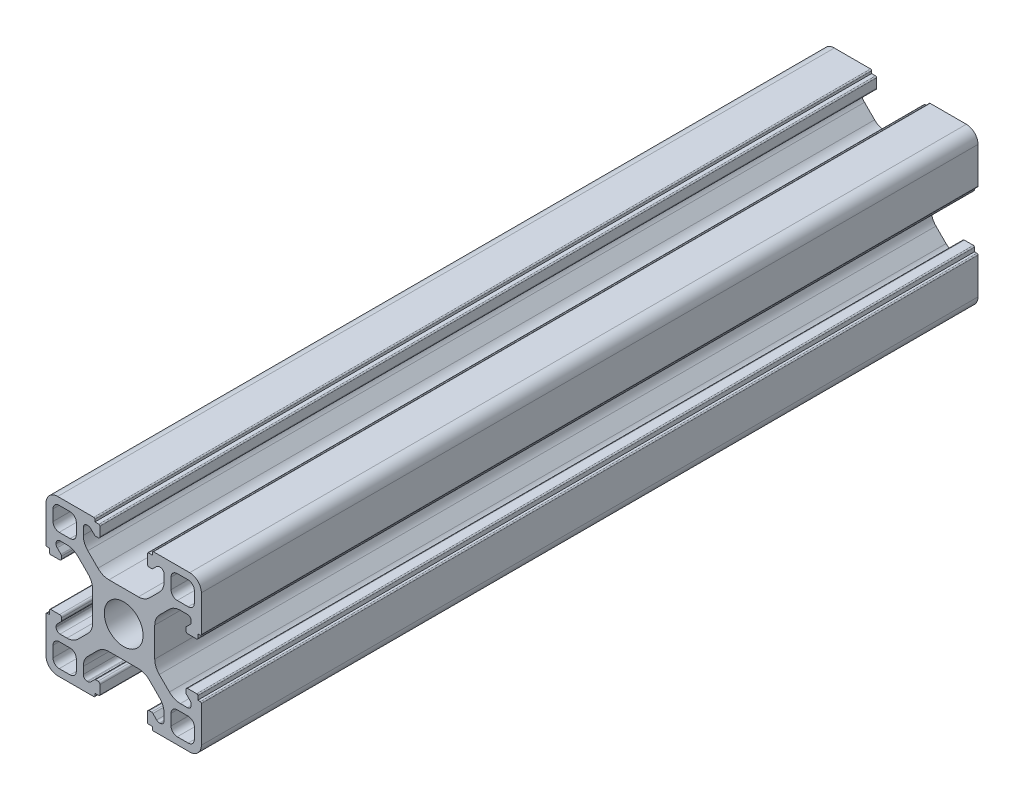
SolidWorks part; units mm, degrees
material "1060 Сплав"
ref_plane "Спереди" through (0, 0, 0) normal (0, 0, 1) x (1, 0, 0)
ref_plane "Сверху" through (0, 0, 0) normal (0, 1, 0) x (1, 0, 0)
ref_plane "Справа" through (0, 0, 0) normal (1, 0, 0) x (0, 0, -1)
sketch "Эскиз1" plane through (0, 0, 0) normal (0, 0, 1) x (1, 0, 0)
  line L0 (9.0997, 9.6536) -> (6.0997, 6.6536) construction
  line L1 (-0.0003, 4.5536) -> (1.8985, 4.5536)
  line L2 (-0.0003, 0.5536) -> (9.9997, 10.5536) construction
  line L3 (7.5997, 8.1536) -> (6.0997, 9.6536) construction
  line L4 (3.3127, 5.1394) -> (4.6139, 6.4406)
  line L5 (6.8997, 6.6536) -> (8.2997, 6.6536)
  line L6 (6.0997, 7.4536) -> (6.0997, 8.8536)
  line L7 (8.2997, 9.6536) -> (6.8997, 9.6536)
  line L8 (5.1997, 8.7536) -> (5.1997, 7.8548)
  line L9 (3.7629, 8.6268) -> (4.2433, 9.1071)
  line L10 (3.1997, 10.1027) -> (3.6997, 10.1027)
  line L11 (3.5862, 8.5536) -> (3.2997, 8.5536)
  line L12 (4.5968, 9.2536) -> (4.6997, 9.2536)
  line L13 (3.6997, 10.4036) -> (3.6997, 10.1027)
  line L14 (3.0497, 9.9527) -> (3.0497, 8.8036)
  line L15 (8.4997, 10.5536) -> (3.8497, 10.5536)
  line L16 (9.0997, 8.8536) -> (9.0997, 7.4536)
  line L17 (9.9997, 9.0536) -> (9.9997, 4.4036)
  line L18 (9.3988, 3.6036) -> (8.2497, 3.6036)
  line L19 (9.8497, 4.2536) -> (9.5488, 4.2536)
  line L20 (8.6997, 5.1507) -> (8.6997, 5.2536)
  line L21 (7.9997, 4.14) -> (7.9997, 3.8536)
  line L22 (9.5488, 3.7536) -> (9.5488, 4.2536)
  line L23 (8.0729, 4.3168) -> (8.5533, 4.7971)
  line L24 (8.1997, 5.7536) -> (7.3009, 5.7536)
  line L25 (4.5855, 3.8666) -> (5.8867, 5.1678)
  line L26 (3.9997, 0.5536) -> (3.9997, 2.4524)
  line L27 (3.9997, 0.5536) -> (3.9997, -1.3452)
  line L28 (4.5855, -2.7594) -> (5.8867, -4.0606)
  line L29 (6.0997, -6.3464) -> (6.0997, -7.7464)
  line L30 (6.8997, -5.5464) -> (8.2997, -5.5464)
  line L31 (9.0997, -7.7464) -> (9.0997, -6.3464)
  line L32 (8.1997, -4.6464) -> (7.3009, -4.6464)
  line L33 (8.0729, -3.2096) -> (8.5533, -3.69)
  line L34 (9.5488, -2.6464) -> (9.5488, -3.1464)
  line L35 (7.9997, -3.0329) -> (7.9997, -2.7464)
  line L36 (8.6997, -4.0435) -> (8.6997, -4.1464)
  line L37 (9.8497, -3.1464) -> (9.5488, -3.1464)
  line L38 (9.3988, -2.4964) -> (8.2497, -2.4964)
  line L39 (9.9997, -7.9464) -> (9.9997, -3.2964)
  line L40 (8.2997, -8.5464) -> (6.8997, -8.5464)
  line L41 (8.4997, -9.4464) -> (3.8497, -9.4464)
  line L42 (3.0497, -8.8455) -> (3.0497, -7.6964)
  line L43 (3.6997, -9.2964) -> (3.6997, -8.9955)
  line L44 (4.5968, -8.1464) -> (4.6997, -8.1464)
  line L45 (3.5862, -7.4464) -> (3.2997, -7.4464)
  line L46 (3.1997, -8.9955) -> (3.6997, -8.9955)
  line L47 (3.7629, -7.5196) -> (4.2433, -8)
  line L48 (5.1997, -7.6464) -> (5.1997, -6.7476)
  line L49 (3.3127, -4.0322) -> (4.6139, -5.3334)
  line L50 (-0.0003, -3.4464) -> (1.8985, -3.4464)
  line L51 (9.0997, -8.5464) -> (6.0997, -5.5464) construction
  line L52 (-0.0003, 0.5536) -> (9.9997, -9.4464) construction
  line L53 (7.5997, -7.0464) -> (9.0997, -5.5464) construction
  line L54 (-0.0003, -3.4464) -> (-1.8991, -3.4464)
  line L55 (-3.3133, -4.0322) -> (-4.6145, -5.3334)
  line L56 (-6.9003, -5.5464) -> (-8.3003, -5.5464)
  line L57 (-6.1003, -6.3464) -> (-6.1003, -7.7464)
  line L58 (-8.3003, -8.5464) -> (-6.9003, -8.5464)
  line L59 (-5.2003, -7.6464) -> (-5.2003, -6.7476)
  line L60 (-3.7635, -7.5196) -> (-4.2438, -8)
  line L61 (-3.2003, -8.9955) -> (-3.7003, -8.9955)
  line L62 (-3.5867, -7.4464) -> (-3.3003, -7.4464)
  line L63 (-4.5974, -8.1464) -> (-4.7003, -8.1464)
  line L64 (-3.7003, -9.2964) -> (-3.7003, -8.9955)
  line L65 (-3.0503, -8.8455) -> (-3.0503, -7.6964)
  line L66 (-8.5003, -9.4464) -> (-3.8503, -9.4464)
  line L67 (-9.1003, -7.7464) -> (-9.1003, -6.3464)
  line L68 (-10.0003, -7.9464) -> (-10.0003, -3.2964)
  line L69 (-9.3994, -2.4964) -> (-8.2503, -2.4964)
  line L70 (-9.8503, -3.1464) -> (-9.5494, -3.1464)
  line L71 (-8.7003, -4.0435) -> (-8.7003, -4.1464)
  line L72 (-8.0003, -3.0329) -> (-8.0003, -2.7464)
  line L73 (-9.5494, -2.6464) -> (-9.5494, -3.1464)
  line L74 (-8.0735, -3.2096) -> (-8.5538, -3.69)
  line L75 (-8.2003, -4.6464) -> (-7.3015, -4.6464)
  line L76 (-4.5861, -2.7594) -> (-5.8873, -4.0606)
  line L77 (-4.0003, 0.5536) -> (-4.0003, -1.3452)
  line L78 (-9.1003, -8.5464) -> (-6.1003, -5.5464) construction
  line L79 (-0.0003, 0.5536) -> (-10.0003, -9.4464) construction
  line L80 (-7.6003, -7.0464) -> (-6.1003, -8.5464) construction
  line L81 (-4.0003, 0.5536) -> (-4.0003, 2.4524)
  line L82 (-4.5861, 3.8666) -> (-5.8873, 5.1678)
  line L83 (-6.1003, 7.4536) -> (-6.1003, 8.8536)
  line L84 (-6.9003, 6.6536) -> (-8.3003, 6.6536)
  line L85 (-9.1003, 8.8536) -> (-9.1003, 7.4536)
  line L86 (-8.2003, 5.7536) -> (-7.3015, 5.7536)
  line L87 (-8.0735, 4.3168) -> (-8.5538, 4.7971)
  line L88 (-9.5494, 3.7536) -> (-9.5494, 4.2536)
  line L89 (-8.0003, 4.14) -> (-8.0003, 3.8536)
  line L90 (-8.7003, 5.1507) -> (-8.7003, 5.2536)
  line L91 (-9.8503, 4.2536) -> (-9.5494, 4.2536)
  line L92 (-9.3994, 3.6036) -> (-8.2503, 3.6036)
  line L93 (-10.0003, 9.0536) -> (-10.0003, 4.4036)
  line L94 (-8.3003, 9.6536) -> (-6.9003, 9.6536)
  line L95 (-8.5003, 10.5536) -> (-3.8503, 10.5536)
  line L96 (-3.0503, 9.9527) -> (-3.0503, 8.8036)
  line L97 (-3.7003, 10.4036) -> (-3.7003, 10.1027)
  line L98 (-4.5974, 9.2536) -> (-4.7003, 9.2536)
  line L99 (-3.5867, 8.5536) -> (-3.3003, 8.5536)
  line L100 (-3.2003, 10.1027) -> (-3.7003, 10.1027)
  line L101 (-3.7635, 8.6268) -> (-4.2438, 9.1071)
  line L102 (-5.2003, 8.7536) -> (-5.2003, 7.8548)
  line L103 (-3.3133, 5.1394) -> (-4.6145, 6.4406)
  line L104 (-0.0003, 4.5536) -> (-1.8991, 4.5536)
  line L105 (-11.7644, 0.5536) -> (11.5041, 0.5536) construction
  line L106 (-9.1003, 9.6536) -> (-6.1003, 6.6536) construction
  line L107 (-0.0003, -11.5328) -> (-0.0003, 11.2725) construction
  line L108 (-0.0003, 0.5536) -> (-10.0003, 10.5536) construction
  line L109 (-7.6003, 8.1536) -> (-9.1003, 6.6536) construction
  arc A0 (9.0997, 8.8536) -> (8.2997, 9.6536) centre (8.2997, 8.8536) ccw
  arc A1 (6.8997, 9.6536) -> (6.0997, 8.8536) centre (6.8997, 8.8536) ccw
  arc A2 (6.8997, 6.6536) -> (6.0997, 7.4536) centre (6.8997, 7.4536) cw
  arc A3 (8.4997, 10.5536) -> (9.9997, 9.0536) centre (8.4997, 9.0536) cw
  arc A4 (3.1997, 10.1027) -> (3.0497, 9.9527) centre (3.1997, 9.9527) ccw
  arc A5 (3.8497, 10.5536) -> (3.6997, 10.4036) centre (3.8497, 10.4036) ccw
  arc A6 (3.5862, 8.5536) -> (3.7629, 8.6268) centre (3.5862, 8.8036) ccw
  arc A7 (3.2997, 8.5536) -> (3.0497, 8.8036) centre (3.2997, 8.8036) cw
  arc A8 (4.2433, 9.1071) -> (4.5968, 9.2536) centre (4.5968, 8.7536) cw
  arc A9 (4.6997, 9.2536) -> (5.1997, 8.7536) centre (4.6997, 8.7536) cw
  arc A10 (2.4997, 0.5536) -> (-0.0003, 3.0536) centre (-0.0003, 0.5536) ccw
  arc A11 (1.8985, 4.5536) -> (3.3127, 5.1394) centre (1.8985, 6.5536) ccw
  arc A12 (5.1997, 7.8548) -> (4.6139, 6.4406) centre (3.1997, 7.8548) cw
  arc A13 (9.0997, 7.4536) -> (8.2997, 6.6536) centre (8.2997, 7.4536) cw
  arc A14 (8.6997, 5.2536) -> (8.1997, 5.7536) centre (8.1997, 5.2536) ccw
  arc A15 (8.5533, 4.7971) -> (8.6997, 5.1507) centre (8.1997, 5.1507) ccw
  arc A16 (7.9997, 3.8536) -> (8.2497, 3.6036) centre (8.2497, 3.8536) ccw
  arc A17 (7.9997, 4.14) -> (8.0729, 4.3168) centre (8.2497, 4.14) cw
  arc A18 (9.9997, 4.4036) -> (9.8497, 4.2536) centre (9.8497, 4.4036) cw
  arc A19 (9.5488, 3.7536) -> (9.3988, 3.6036) centre (9.3988, 3.7536) cw
  arc A20 (7.3009, 5.7536) -> (5.8867, 5.1678) centre (7.3009, 3.7536) ccw
  arc A21 (3.9997, 2.4524) -> (4.5855, 3.8666) centre (5.9997, 2.4524) cw
  arc A22 (8.2997, -8.5464) -> (9.0997, -7.7464) centre (8.2997, -7.7464) ccw
  arc A23 (9.0997, -6.3464) -> (8.2997, -5.5464) centre (8.2997, -6.3464) ccw
  arc A24 (6.0997, -6.3464) -> (6.8997, -5.5464) centre (6.8997, -6.3464) cw
  arc A25 (9.9997, -7.9464) -> (8.4997, -9.4464) centre (8.4997, -7.9464) cw
  arc A26 (9.5488, -2.6464) -> (9.3988, -2.4964) centre (9.3988, -2.6464) ccw
  arc A27 (9.9997, -3.2964) -> (9.8497, -3.1464) centre (9.8497, -3.2964) ccw
  arc A28 (7.9997, -3.0329) -> (8.0729, -3.2096) centre (8.2497, -3.0329) ccw
  arc A29 (7.9997, -2.7464) -> (8.2497, -2.4964) centre (8.2497, -2.7464) cw
  arc A30 (8.5533, -3.69) -> (8.6997, -4.0435) centre (8.1997, -4.0435) cw
  arc A31 (8.6997, -4.1464) -> (8.1997, -4.6464) centre (8.1997, -4.1464) cw
  arc A32 (-0.0003, -1.9464) -> (2.4997, 0.5536) centre (-0.0003, 0.5536) ccw
  arc A33 (3.9997, -1.3452) -> (4.5855, -2.7594) centre (5.9997, -1.3452) ccw
  arc A34 (7.3009, -4.6464) -> (5.8867, -4.0606) centre (7.3009, -2.6464) cw
  arc A35 (6.8997, -8.5464) -> (6.0997, -7.7464) centre (6.8997, -7.7464) cw
  arc A36 (4.6997, -8.1464) -> (5.1997, -7.6464) centre (4.6997, -7.6464) ccw
  arc A37 (4.2433, -8) -> (4.5968, -8.1464) centre (4.5968, -7.6464) ccw
  arc A38 (3.2997, -7.4464) -> (3.0497, -7.6964) centre (3.2997, -7.6964) ccw
  arc A39 (3.5862, -7.4464) -> (3.7629, -7.5196) centre (3.5862, -7.6964) cw
  arc A40 (3.8497, -9.4464) -> (3.6997, -9.2964) centre (3.8497, -9.2964) cw
  arc A41 (3.1997, -8.9955) -> (3.0497, -8.8455) centre (3.1997, -8.8455) cw
  arc A42 (5.1997, -6.7476) -> (4.6139, -5.3334) centre (3.1997, -6.7476) ccw
  arc A43 (1.8985, -3.4464) -> (3.3127, -4.0322) centre (1.8985, -5.4464) cw
  arc A44 (-9.1003, -7.7464) -> (-8.3003, -8.5464) centre (-8.3003, -7.7464) ccw
  arc A45 (-6.9003, -8.5464) -> (-6.1003, -7.7464) centre (-6.9003, -7.7464) ccw
  arc A46 (-6.9003, -5.5464) -> (-6.1003, -6.3464) centre (-6.9003, -6.3464) cw
  arc A47 (-8.5003, -9.4464) -> (-10.0003, -7.9464) centre (-8.5003, -7.9464) cw
  arc A48 (-3.2003, -8.9955) -> (-3.0503, -8.8455) centre (-3.2003, -8.8455) ccw
  arc A49 (-3.8503, -9.4464) -> (-3.7003, -9.2964) centre (-3.8503, -9.2964) ccw
  arc A50 (-3.5867, -7.4464) -> (-3.7635, -7.5196) centre (-3.5867, -7.6964) ccw
  arc A51 (-3.3003, -7.4464) -> (-3.0503, -7.6964) centre (-3.3003, -7.6964) cw
  arc A52 (-4.2438, -8) -> (-4.5974, -8.1464) centre (-4.5974, -7.6464) cw
  arc A53 (-4.7003, -8.1464) -> (-5.2003, -7.6464) centre (-4.7003, -7.6464) cw
  arc A54 (-2.5003, 0.5536) -> (-0.0003, -1.9464) centre (-0.0003, 0.5536) ccw
  arc A55 (-1.8991, -3.4464) -> (-3.3133, -4.0322) centre (-1.8991, -5.4464) ccw
  arc A56 (-5.2003, -6.7476) -> (-4.6145, -5.3334) centre (-3.2003, -6.7476) cw
  arc A57 (-9.1003, -6.3464) -> (-8.3003, -5.5464) centre (-8.3003, -6.3464) cw
  arc A58 (-8.7003, -4.1464) -> (-8.2003, -4.6464) centre (-8.2003, -4.1464) ccw
  arc A59 (-8.5538, -3.69) -> (-8.7003, -4.0435) centre (-8.2003, -4.0435) ccw
  arc A60 (-8.0003, -2.7464) -> (-8.2503, -2.4964) centre (-8.2503, -2.7464) ccw
  arc A61 (-8.0003, -3.0329) -> (-8.0735, -3.2096) centre (-8.2503, -3.0329) cw
  arc A62 (-10.0003, -3.2964) -> (-9.8503, -3.1464) centre (-9.8503, -3.2964) cw
  arc A63 (-9.5494, -2.6464) -> (-9.3994, -2.4964) centre (-9.3994, -2.6464) cw
  arc A64 (-7.3015, -4.6464) -> (-5.8873, -4.0606) centre (-7.3015, -2.6464) ccw
  arc A65 (-4.0003, -1.3452) -> (-4.5861, -2.7594) centre (-6.0003, -1.3452) cw
  arc A66 (-8.3003, 9.6536) -> (-9.1003, 8.8536) centre (-8.3003, 8.8536) ccw
  arc A67 (-9.1003, 7.4536) -> (-8.3003, 6.6536) centre (-8.3003, 7.4536) ccw
  arc A68 (-6.1003, 7.4536) -> (-6.9003, 6.6536) centre (-6.9003, 7.4536) cw
  arc A69 (-10.0003, 9.0536) -> (-8.5003, 10.5536) centre (-8.5003, 9.0536) cw
  arc A70 (-9.5494, 3.7536) -> (-9.3994, 3.6036) centre (-9.3994, 3.7536) ccw
  arc A71 (-10.0003, 4.4036) -> (-9.8503, 4.2536) centre (-9.8503, 4.4036) ccw
  arc A72 (-8.0003, 4.14) -> (-8.0735, 4.3168) centre (-8.2503, 4.14) ccw
  arc A73 (-8.0003, 3.8536) -> (-8.2503, 3.6036) centre (-8.2503, 3.8536) cw
  arc A74 (-8.5538, 4.7971) -> (-8.7003, 5.1507) centre (-8.2003, 5.1507) cw
  arc A75 (-8.7003, 5.2536) -> (-8.2003, 5.7536) centre (-8.2003, 5.2536) cw
  arc A76 (-0.0003, 3.0536) -> (-2.5003, 0.5536) centre (-0.0003, 0.5536) ccw
  arc A77 (-4.0003, 2.4524) -> (-4.5861, 3.8666) centre (-6.0003, 2.4524) ccw
  arc A78 (-7.3015, 5.7536) -> (-5.8873, 5.1678) centre (-7.3015, 3.7536) cw
  arc A79 (-6.9003, 9.6536) -> (-6.1003, 8.8536) centre (-6.9003, 8.8536) cw
  arc A80 (-4.7003, 9.2536) -> (-5.2003, 8.7536) centre (-4.7003, 8.7536) ccw
  arc A81 (-4.2438, 9.1071) -> (-4.5974, 9.2536) centre (-4.5974, 8.7536) ccw
  arc A82 (-3.3003, 8.5536) -> (-3.0503, 8.8036) centre (-3.3003, 8.8036) ccw
  arc A83 (-3.5867, 8.5536) -> (-3.7635, 8.6268) centre (-3.5867, 8.8036) cw
  arc A84 (-3.8503, 10.5536) -> (-3.7003, 10.4036) centre (-3.8503, 10.4036) cw
  arc A85 (-3.2003, 10.1027) -> (-3.0503, 9.9527) centre (-3.2003, 9.9527) cw
  arc A86 (-5.2003, 7.8548) -> (-4.6145, 6.4406) centre (-3.2003, 7.8548) ccw
  arc A87 (-1.8991, 4.5536) -> (-3.3133, 5.1394) centre (-1.8991, 6.5536) cw
  point P0 (-0.0003, 0.5536)
  point P9 (-0.0003, 0.5536)
  point P40 (8.6997, 4.2536)
  point P93 (3.6997, -8.1464)
  point P144 (3.6997, 9.2536)
  point P152 (8.6997, -3.1464)
  point P153 (-0.0003, -3.3707)
  point P154 (-0.0003, 0.5536)
  point P189 (-8.7003, -3.1464)
  point P228 (-3.7003, -8.1464)
  point P229 (-3.9246, 0.5536)
  point P230 (-0.0003, 0.5536)
  point P268 (-3.7003, 9.2536)
  point P273 (3.924, 0.5536)
  point P306 (-8.7003, 4.2536)
  point P307 (-0.0003, 4.4778)
  point P309 (-0.0003, 0.5536)
  point P310 (0, 0)
  point P311 (0, 0)
  point P312 (0, 0)
  point P313 (0, 0)
  dimension "D2" = 5
  dimension "D5" = 2
  dimension "D1" = 6
  dimension "D3" = 4
  dimension "D4" = 0.9
extrude "Бобышка-Вытянуть1" add sketch "Эскиз1" along normal blind 100
